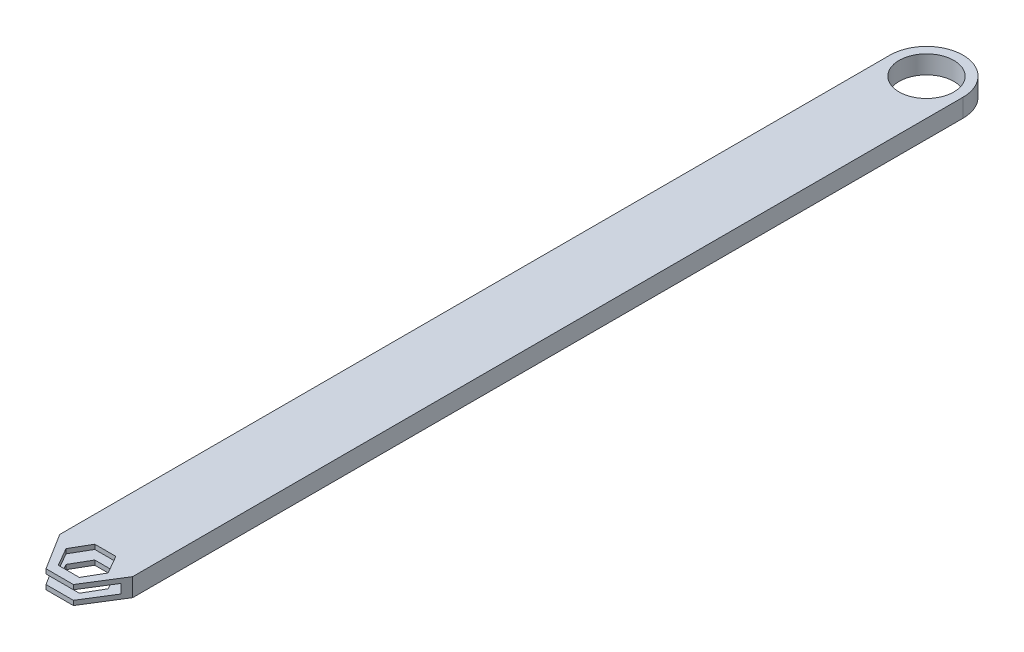
SolidWorks part; units mm, degrees
material "6061 Alloy"
ref_plane "Front Plane" through (0, 0, 0) normal (0, 0, 1) x (1, 0, 0)
ref_plane "Top Plane" through (0, 0, 0) normal (0, 1, 0) x (1, 0, 0)
ref_plane "Right Plane" through (0, 0, 0) normal (1, 0, 0) x (0, 0, -1)
sketch "Sketch1" plane through (0, 0, 0) normal (0, 0, 1) x (1, 0, 0)
  line L1 (0, 0) -> (25.4, 0)
  line L2 (0, 0) -> (0, 6.35)
  line L3 (0, 6.35) -> (25.4, 6.35)
  line L4 (25.4, 0) -> (25.4, 6.35)
  dimension "D1" = 25.4
  dimension "D2" = 6.35
extrude "Boss-Extrude1" add sketch "Sketch1" along normal blind 304.8
sketch "Sketch2" plane through (0, 0, 304.8) normal (0, 0, 1) x (1, 0, 0)
  line L4 (23.8125, 1.5875) -> (23.8125, 4.7625)
  line L5 (23.8125, 1.5875) -> (23.8125, 4.7625)
  line L6 (1.5875, 4.7625) -> (1.5875, 1.5875)
  line L7 (1.5875, 4.7625) -> (1.5875, 1.5875)
  line L8 (23.8125, 4.7625) -> (1.5875, 4.7625)
  line L9 (1.5875, 1.5875) -> (23.8125, 1.5875)
  line L10 (23.8125, 4.7625) -> (1.5875, 4.7625)
  line L13 (1.5875, 1.5875) -> (23.8125, 1.5875)
  dimension "D1" = 1.5875
extrude "Cut-Extrude1" cut sketch "Sketch2" against normal through all
sketch "Sketch3" plane through (0, 0, 0) normal (0, -1, 0) x (1, 0, 0)
  line L0 (25.4, 304.8) -> (25.4, 0) construction
  line L1 (20.0323, 292.1) -> (16.3662, 298.45)
  line L2 (16.3662, 298.45) -> (9.0338, 298.45)
  line L3 (9.0338, 298.45) -> (5.3677, 292.1)
  line L4 (5.3677, 292.1) -> (9.0338, 285.75)
  line L5 (9.0338, 285.75) -> (16.3662, 285.75)
  line L6 (16.3662, 285.75) -> (20.0323, 292.1)
  line L8 (0, 304.8) -> (25.4, 304.8) construction
  circle A0 centre (12.7, 292.1) radius 6.35 construction
  dimension "D3" = 12.7
  dimension "D1" = 12.7
  dimension "D2" = 12.7
extrude "Cut-Extrude2" cut sketch "Sketch3" against normal through all
sketch "Sketch4" plane through (0, 6.35, 0) normal (0, 1, 0) x (1, 0, 0)
  line L0 (0, -288.925) -> (7.9375, -301.625)
  line L1 (0, -304.8) -> (0, 0) construction
  line L2 (7.9375, -301.625) -> (17.4625, -301.625)
  line L3 (17.4625, -301.625) -> (25.4, -288.925)
  line L4 (25.4, -304.8) -> (25.4, 0) construction
  line L5 (16.3662, -298.45) -> (9.0338, -298.45) construction
  line L7 (25.4, -288.925) -> (25.4, -304.8)
  line L8 (25.4, -304.8) -> (0, -304.8)
  line L9 (0, -304.8) -> (0, -288.925)
  point P8 (12.7, -301.625)
  point P11 (12.7, -298.45)
  dimension "D1" = 3.175
  dimension "D2" = 15.875
  dimension "D3" = 15.875
  dimension "D4" = 9.525
extrude "Cut-Extrude3" cut sketch "Sketch4" against normal through all
sketch "Sketch5" plane through (0, 6.35, 0) normal (0, 1, 0) x (1, 0, 0)
  line L0 (25.4, 0) -> (0, 0) construction
  circle A0 centre (12.7, 0) radius 12.7
extrude "Boss-Extrude2" add sketch "Sketch5" against normal blind 6.35
sketch "Sketch6" plane through (0, 6.35, 0) normal (0, 1, 0) x (1, 0, 0)
  circle A0 centre (12.7, 0) radius 9.525
  dimension "D1" = 19.05
extrude "Cut-Extrude4" cut sketch "Sketch6" against normal through all
